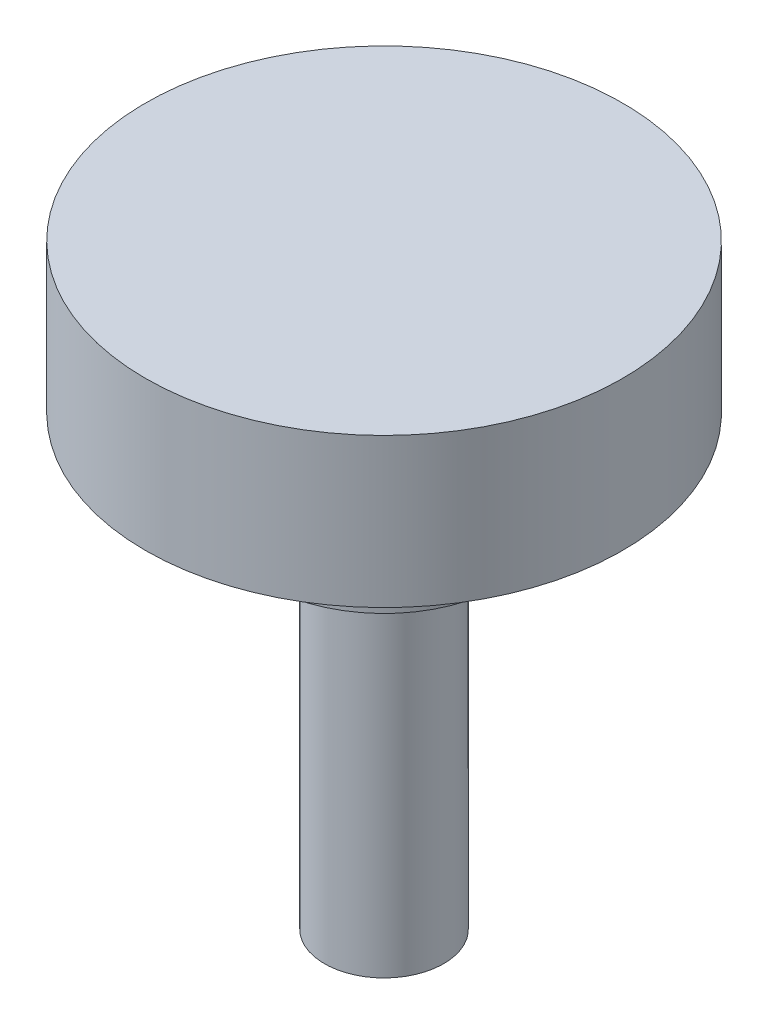
SolidWorks part; units mm, degrees
ref_plane "Front Plane" through (0, 0, 0) normal (0, 0, 1) x (1, 0, 0)
ref_plane "Top Plane" through (0, 0, 0) normal (0, 1, 0) x (1, 0, 0)
ref_plane "Right Plane" through (0, 0, 0) normal (1, 0, 0) x (0, 0, -1)
sketch "Sketch1" plane through (0, 0, 0) normal (0, 1, 0) x (1, 0, 0)
  circle A0 centre (0, 0) radius 3.175
  dimension "D1" = 6.35
extrude "Boss-Extrude1" add sketch "Sketch1" along normal blind 19.05
sketch "Sketch2" plane through (0, 19.05, 0) normal (0, 1, 0) x (1, 0, 0)
  circle A0 centre (0, 0) radius 6.35
  dimension "D1" = 12.7
extrude "Boss-Extrude2" add sketch "Sketch2" along normal blind 4.7625
sketch "Sketch3" plane through (0, 23.8125, 0) normal (0, 1, 0) x (1, 0, 0)
  circle A0 centre (0, 0) radius 12.7
  dimension "D1" = 25.4
extrude "Boss-Extrude3" add sketch "Sketch3" along normal blind 7.9375
